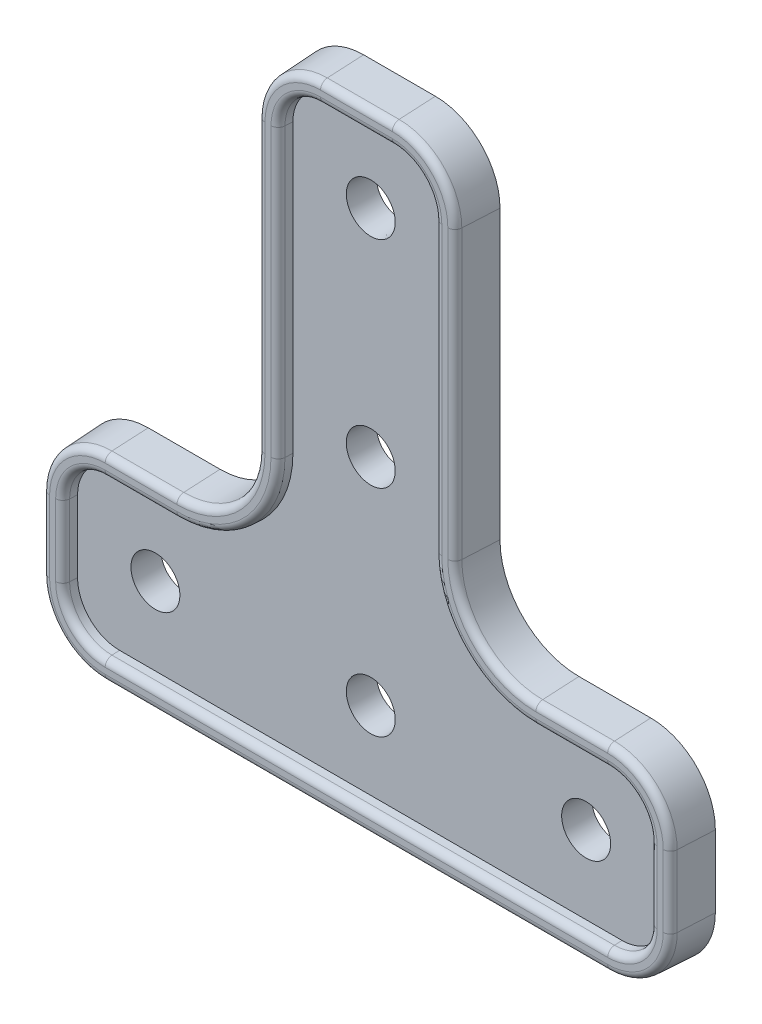
SolidWorks part; units mm, degrees
ref_plane "Front Plane" through (0, 0, 0) normal (0, 0, 1) x (1, 0, 0)
ref_plane "Top Plane" through (0, 0, 0) normal (0, 1, 0) x (1, 0, 0)
ref_plane "Right Plane" through (0, 0, 0) normal (1, 0, 0) x (0, 0, -1)
sketch "Sketch1" plane through (0, 0, 0) normal (0, 0, 1) x (1, 0, 0)
  line L0 (55, 0) -> (-55, 0) construction
  line L1 (-7.5, 30) -> (7.5, 30)
  line L2 (-7.5, 30) -> (-7.5, 0)
  line L3 (7.5, 0) -> (22.5, 0)
  line L4 (7.5, 30) -> (7.5, 0)
  line L5 (-22.5, 0) -> (-7.5, 0)
  line L6 (-22.5, 0) -> (-22.5, -15)
  line L7 (-22.5, -15) -> (22.5, -15)
  line L8 (22.5, 0) -> (22.5, -15)
  line L9 (0, 49.321) -> (0, -31.3726) construction
  line L10 (0, -54.6431) -> (0, 54.6431) construction
  dimension "D1" = 15
  dimension "D2" = 45
  dimension "D3" = 45
extrude "Boss-Extrude1" add sketch "Sketch1" along normal blind 2
fillet "Fillet1" radius 5 8 edges at (22.5, -15, 1) (22.5, 0, 1) (-7.5, 0, 1) (7.5, 0, 1) (7.5, 30, 1) (-22.5, -15, 1) (-22.5, 0, 1) (-7.5, 30, 1)
sketch "Sketch2" plane through (0, 0, 2) normal (0, 0, 1) x (1, 0, 0)
  line L0 (-22.5, -7.5) -> (22.5, -7.5) construction
  line L1 (-22.5, -5) -> (-22.5, -10) construction
  line L2 (22.5, -10) -> (22.5, -5) construction
  line L3 (0, 30) -> (0, -15) construction
  line L4 (2.5, 30) -> (-2.5, 30) construction
  line L5 (-17.5, -15) -> (17.5, -15) construction
  circle A0 centre (-15, -7.5) radius 1.6
  circle A1 centre (0, -7.5) radius 1.6
  circle A2 centre (15, -7.5) radius 1.6
  circle A3 centre (0, 22.5) radius 1.6
  circle A4 centre (0, 7.5) radius 1.6
  dimension "D1" = 3.2
  dimension "D2" = 15
  dimension "D3" = 15
  dimension "D4" = 15
  dimension "D5" = 15
extrude "Cut-Extrude1" cut sketch "Sketch2" against normal through all
other "Move Face1" face at (-9.4822, 1.9822, 1) face at (-15, 0, 1) face at (-20.5178, -1.9822, 1) face at (-22.5, -7.5, 1) face at (-20.5178, -13.0178, 1) face at (0, -15, 1) face at (20.5178, -13.0178, 1) face at (22.5, -7.5, 1) face at (20.5178, -1.9822, 1) face at (15, 0, 1) face at (9.4822, 1.9822, 1) face at (7.5, 15, 1) face at (5.5178, 28.0178, 1) face at (0, 30, 1) face at (-5.5178, 28.0178, 1) face at (-7.5, 15, 1) parameters "D1"=0.5
draft "Draft1" type of draft neutral plane draft angle 3 faces to draft 21 face at (16.6, -7.5, 0) face at (1.6, 22.5, 0) face at (1.6, 7.5, 0) face at (1.6, -7.5, 0) face at (-13.4, -7.5, 0) face at (-20.216, -2.284, 1) face at (-22, -7.5, 1) face at (-20.216, -12.716, 1) face at (0, -14.5, 1) face at (20.216, -12.716, 1) face at (22, -7.5, 1) face at (20.216, -2.284, 1) face at (15, -0.5, 1) face at (9.1805, 1.6805, 1) face at (7, 15, 1) face at (5.216, 27.716, 1) face at (0, 29.5, 1) face at (-5.216, 27.716, 1) face at (-7, 15, 1) face at (-9.1805, 1.6805, 1) face at (-15, -0.5, 1) neutral plane through (0, 0, 0) neutral plane normal (0, 0, -1) reverse direction yes parameters "D1"=3
sketch "Sketch4" plane through (0, 0, 2) normal (0, 0, 1) x (1, 0, 0)
  line L0 (-17.5, -12.9214) -> (17.5, -12.9214)
  line L1 (20.4214, -10) -> (20.4214, -5)
  line L2 (17.5, -2.0786) -> (12.5, -2.0786)
  line L3 (5.4214, 5) -> (5.4214, 25)
  line L4 (2.5, 27.9214) -> (-2.5, 27.9214)
  line L5 (-5.4214, 25) -> (-5.4214, 5)
  line L6 (-12.5, -2.0786) -> (-17.5, -2.0786)
  line L7 (-20.4214, -5) -> (-20.4214, -10)
  line L8 (-17.5, -14.3952) -> (17.5, -14.3952)
  line L9 (21.8952, -10) -> (21.8952, -5)
  line L10 (17.5, -0.6048) -> (12.5, -0.6048)
  line L11 (6.8952, 5) -> (6.8952, 25)
  line L12 (2.5, 29.3952) -> (-2.5, 29.3952)
  line L13 (-6.8952, 25) -> (-6.8952, 5)
  line L14 (-12.5, -0.6048) -> (-17.5, -0.6048)
  line L15 (-21.8952, -5) -> (-21.8952, -10)
  line L16 (-17.5, -14.3952) -> (17.5, -14.3952)
  line L17 (21.8952, -10) -> (21.8952, -5)
  line L18 (17.5, -0.6048) -> (12.5, -0.6048)
  line L19 (6.8952, 5) -> (6.8952, 25)
  line L20 (2.5, 29.3952) -> (-2.5, 29.3952)
  line L21 (-6.8952, 25) -> (-6.8952, 5)
  line L22 (-12.5, -0.6048) -> (-17.5, -0.6048)
  line L23 (-21.8952, -5) -> (-21.8952, -10)
  arc A2 (17.5, -12.9214) -> (20.4214, -10) centre (17.5, -10) ccw
  arc A3 (20.4214, -5) -> (17.5, -2.0786) centre (17.5, -5) ccw
  arc A4 (5.4214, 5) -> (12.5, -2.0786) centre (12.5, 5) ccw
  arc A5 (5.4214, 25) -> (2.5, 27.9214) centre (2.5, 25) ccw
  arc A6 (-2.5, 27.9214) -> (-5.4214, 25) centre (-2.5, 25) ccw
  arc A7 (-12.5, -2.0786) -> (-5.4214, 5) centre (-12.5, 5) ccw
  arc A8 (-17.5, -2.0786) -> (-20.4214, -5) centre (-17.5, -5) ccw
  arc A9 (-20.4214, -10) -> (-17.5, -12.9214) centre (-17.5, -10) ccw
  arc A10 (17.5, -14.3952) -> (21.8952, -10) centre (17.5, -10) ccw
  arc A11 (21.8952, -5) -> (17.5, -0.6048) centre (17.5, -5) ccw
  arc A12 (6.8952, 5) -> (12.5, -0.6048) centre (12.5, 5) ccw
  arc A13 (6.8952, 25) -> (2.5, 29.3952) centre (2.5, 25) ccw
  arc A14 (-2.5, 29.3952) -> (-6.8952, 25) centre (-2.5, 25) ccw
  arc A15 (-12.5, -0.6048) -> (-6.8952, 5) centre (-12.5, 5) ccw
  arc A16 (-17.5, -0.6048) -> (-21.8952, -5) centre (-17.5, -5) ccw
  arc A17 (-21.8952, -10) -> (-17.5, -14.3952) centre (-17.5, -10) ccw
  arc A18 (17.5, -14.3952) -> (21.8952, -10) centre (17.5, -10) ccw
  arc A19 (21.8952, -5) -> (17.5, -0.6048) centre (17.5, -5) ccw
  arc A20 (6.8952, 5) -> (12.5, -0.6048) centre (12.5, 5) ccw
  arc A21 (6.8952, 25) -> (2.5, 29.3952) centre (2.5, 25) ccw
  arc A22 (-2.5, 29.3952) -> (-6.8952, 25) centre (-2.5, 25) ccw
  arc A23 (-12.5, -0.6048) -> (-6.8952, 5) centre (-12.5, 5) ccw
  arc A24 (-17.5, -0.6048) -> (-21.8952, -5) centre (-17.5, -5) ccw
  arc A25 (-21.8952, -10) -> (-17.5, -14.3952) centre (-17.5, -10) ccw
  dimension "D1" = 0
extrude "Boss-Extrude3" add sketch "Sketch4" along normal blind 1 draft 3
fillet "Fillet3" radius 0.5 32 edges at (-20.5708, -13.0708, 3) (0, -14.3428, 3) (20.5708, -13.0708, 3) (21.8428, -7.5, 3) (20.5708, -1.9292, 3) (15, -0.6572, 3) (8.4997, 0.9997, 3) (6.8428, 15, 3) (5.5708, 28.0708, 3) (0, 29.3428, 3) (-5.5708, 28.0708, 3) (-6.8428, 15, 3) (-8.4997, 0.9997, 3) (-15, -0.6572, 3) (-20.5708, -1.9292, 3) (-21.8428, -7.5, 3) (-19.6028, -12.1028, 3) (0, -12.9738, 3) (19.6028, -12.1028, 3) (20.4738, -7.5, 3) (19.6028, -2.8972, 3) (15, -2.0262, 3) (7.5317, 0.0317, 3) (5.4738, 15, 3) (4.6028, 27.1028, 3) (0, 27.9738, 3) (-4.6028, 27.1028, 3) (-5.4738, 15, 3) (-7.5317, 0.0317, 3) (-15, -2.0262, 3) (-19.6028, -2.8972, 3) (-20.4738, -7.5, 3)
sketch "Sketch5" plane through (0, 0, 0) normal (0, 0, -1) x (-1, 0, 0)
  line L0 (0, 54.6431) -> (0, -54.6431) construction
  line L1 (-14.5, -13.8) -> (14.5, -13.8)
  line L2 (-15, -13.3) -> (-15, -10.3)
  line L3 (-14.5, -9.8) -> (14.5, -9.8)
  line L4 (15, -13.3) -> (15, -10.3)
  line L5 (-15, -13.8) -> (15, -9.8) construction
  line L6 (-15, -9.8) -> (15, -13.8) construction
  line L7 (17.5, -14.5) -> (-17.5, -14.5) construction
  arc A0 (14.5, -13.8) -> (15, -13.3) centre (14.5, -13.3) ccw
  arc A1 (14.5, -9.8) -> (15, -10.3) centre (14.5, -10.3) cw
  arc A2 (-14.5, -13.8) -> (-15, -13.3) centre (-14.5, -13.3) cw
  arc A3 (-15, -10.3) -> (-14.5, -9.8) centre (-14.5, -10.3) cw
  point P0 (0, -11.8)
  dimension "D4" = 0.5
  dimension "D1" = 30
  dimension "D2" = 4
  dimension "D3" = 0.7
extrude "Cut-Extrude2" cut sketch "Sketch5" against normal blind 0.2 draft 3
